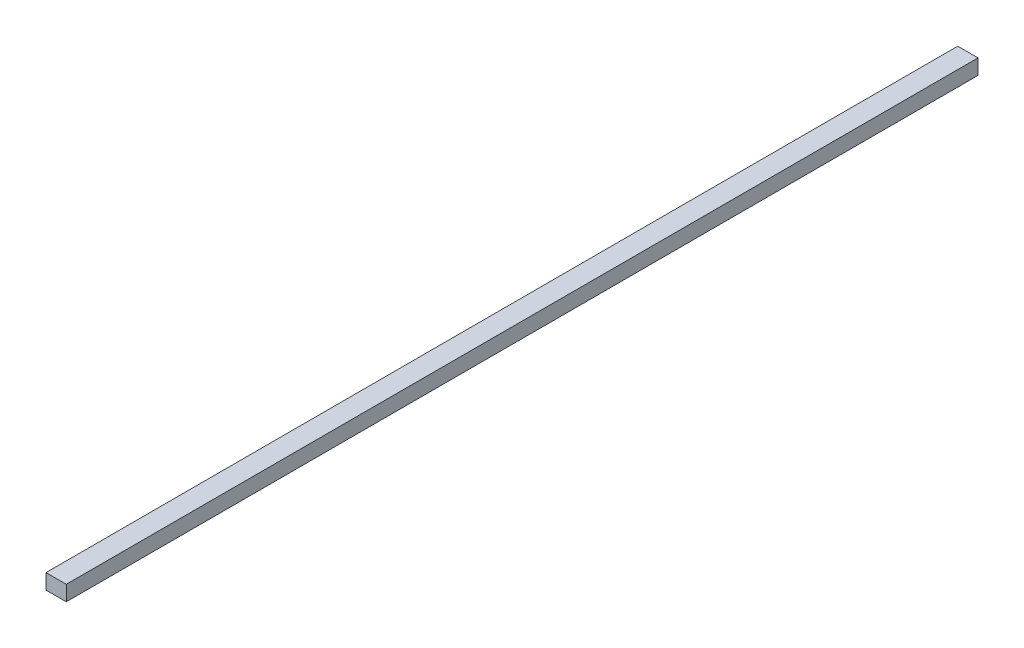
SolidWorks part; units mm, degrees
material "Pine"
ref_plane "Piano frontale" through (0, 0, 0) normal (0, 0, 1) x (1, 0, 0)
ref_plane "Piano superiore" through (0, 0, 0) normal (0, 1, 0) x (1, 0, 0)
ref_plane "Piano destro" through (0, 0, 0) normal (1, 0, 0) x (0, 0, -1)
sketch "Sketch1" plane through (0, 0, 0) normal (0, 0, 1) x (1, 0, 0)
  line L1 (0, 0) -> (2, 0)
  line L2 (0, 0) -> (0, 1.5)
  line L3 (0, 1.5) -> (2, 1.5)
  line L4 (2, 0) -> (2, 1.5)
  dimension "D1" = 2
  dimension "D2" = 1.5
extrude "Boss-Extrude1" add sketch "Sketch1" along normal blind 90
scale "Scale1" scale about origin uniform scaling yes scale factor 10
